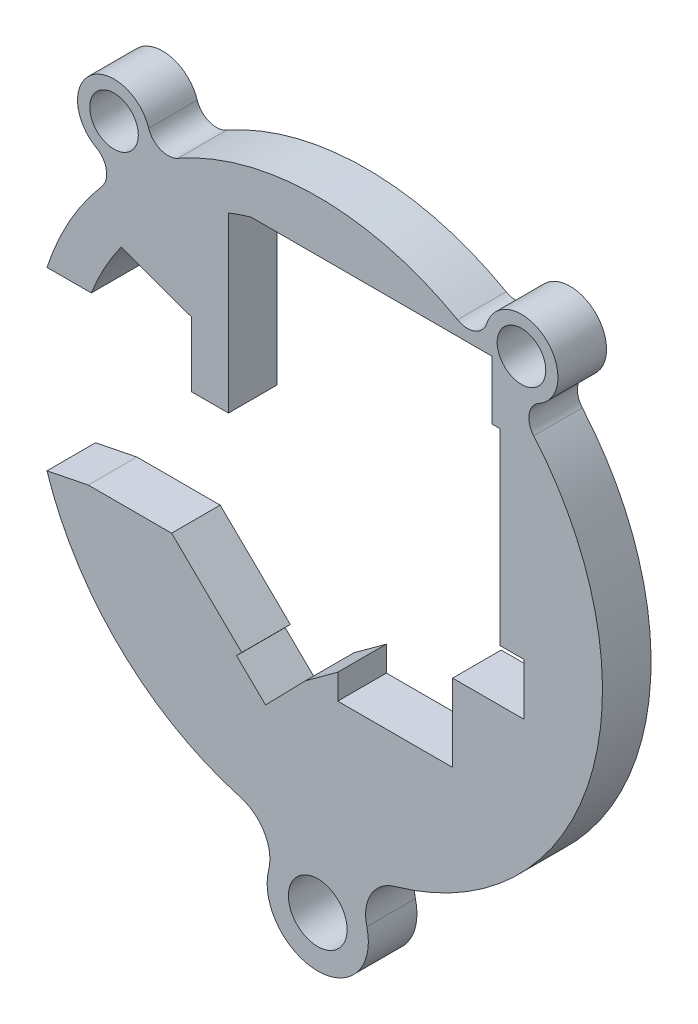
SolidWorks part; units mm, degrees
ref_plane "Front Plane" through (0, 0, 0) normal (0, 0, 1) x (1, 0, 0)
ref_plane "Top Plane" through (0, 0, 0) normal (0, 1, 0) x (1, 0, 0)
ref_plane "Right Plane" through (0, 0, 0) normal (1, 0, 0) x (0, 0, -1)
sketch "Sketch1" plane through (0, 0, 0) normal (0, 0, 1) x (1, 0, 0)
  line L1 (-14.9521, -2.9485) -> (-16.9841, -2.9485)
  line L2 (-16.9841, 2.9485) -> (-16.9841, 5.5245)
  line L3 (-14.9521, 2.9485) -> (-16.9841, 2.9485)
  line L4 (-16.9841, 5.5245) -> (-21.1739, 5.5245)
  line L5 (-16.9841, -2.9485) -> (-16.9841, -5.5245)
  line L6 (-16.9841, -5.5245) -> (-20.8712, -5.5245)
  line L7 (-15.24, 0) -> (-21.59, 0) construction
  line B0 (-15.24, 18.2372) -> (15.24, 18.2372)
  line B1 (11.43, 14.6558) -> (11.43, -0.8128)
  line B2 (0, 18.2372) -> (0, 0) construction
  line B3 (-5.6007, 14.1736) -> (-5.6007, -0.8128)
  line B4 (11.43, 14.6558) -> (-4.1791, 14.6558)
  line B5 (-5.6007, -0.8128) -> (11.43, -0.8128)
  line B6 (8.4582, -4.064) -> (12.9413, -4.064)
  line B7 (11.43, -0.8128) -> (12.9413, -0.8128)
  line B8 (12.9413, -0.8128) -> (12.9413, -4.064)
  line B9 (8.4582, -7.3406) -> (1.2573, -7.3406)
  line B10 (8.4582, -4.064) -> (8.4582, -7.3406)
  line B11 (-4.3942, -0.8128) -> (-4.3942, -4.064)
  line B12 (-4.3942, -4.064) -> (1.2573, -4.064)
  line B13 (1.2573, -4.064) -> (1.2573, -7.3406)
  line B14 (-0.7747, -8.8265) -> (-3.2737, -11.3919)
  line B15 (-0.7747, -8.8265) -> (-2.5941, -7.0541)
  line B16 (-2.5941, -7.0541) -> (-2.9176, -7.3862)
  line B17 (-2.9176, -7.3862) -> (-8.5123, -1.9362)
  line B18 (-8.5123, -1.9362) -> (-10.3645, -3.8375)
  line B19 (-10.3645, -3.8375) -> (-4.7697, -9.2875)
  line B20 (-4.7697, -9.2875) -> (-5.0932, -9.6195)
  line B21 (-5.0932, -9.6195) -> (-3.2737, -11.3919)
  line B22 (-12.3326, 18.2372) -> (-12.3326, 8.9535)
  line B23 (-7.9248, 18.2372) -> (-7.9248, 7.366) construction
  line B24 (-12.3326, 8.9535) -> (-7.9248, 7.366)
  line B25 (-5.6007, 3.302) -> (-7.9248, 3.302)
  line B26 (-7.9248, 3.302) -> (-7.9248, 7.366)
  line B27 (-14.3951, -5.0038) -> (-9.1672, -5.0038)
  line B28 (-0.7747, -8.8265) -> (1.2573, -7.3406)
  arc B29 (-3.302, 14.878) -> (3.302, 14.878) centre (0, 0) ccw
  circle B30 centre (0, -18.415) radius 1.4224
  circle B31 centre (0, 18.415) radius 1.4224
  circle B32 centre (0, 0) radius 21.59
  line B33 (1.2573, -8.9154) -> (8.4582, -8.9154)
  line B34 (1.2573, -7.3406) -> (1.2573, -8.9154)
  line B35 (8.4582, -7.3406) -> (8.4582, -8.9154)
  dimension "D1" = 2.032
  dimension "D2" = 11.049
sketch_block_instance "Block1-1"
sketch_block "Block1" parameters "D1"=3.81, "D2"=30.48, "D3"=3.5814, "D4"=9.6393, "D5"=19.05, "D6"=22.3012, "D7"=1.5113, "D8"=4.4831, "D9"=6.5278, "D10"=7.2009, "D11"=5.6515, "D12"=27.0637, "D13"=29.6291, "D14"=3.5814, "D15"=14.4653, "D16"=2.54, "D17"=2.6543, "D18"=10.3505, "D19"=9.2837, "D20"=10.8712, "D21"=7.3152, "D22"=14.9352, "D23"=23.241
extrude "Boss-Extrude1" add sketch "Sketch1" along normal blind 3.048
sketch "Sketch2" plane through (0, 0, 3.048) normal (0, 0, 1) x (1, 0, 0)
  line L0 (-14.3951, -5.0038) -> (-16.9841, -5.5245)
  line L2 (-16.9841, 5.5245) -> (-14.2034, 5.5245)
  line L3 (-14.3951, -5.0038) -> (-14.2034, 5.5245)
  line L4 (-16.9841, -5.5245) -> (-16.9841, 5.5245)
  arc A0 (-12.3326, 8.9535) -> (-14.9521, 2.9485) centre (0, 0) ccw construction
extrude "Cut-Extrude1" cut sketch "Sketch2" against normal through all
sketch "Sketch3" plane through (0, 0, 3.048) normal (0, 0, 1) x (1, 0, 0)
  line L0 (0, 0) -> (11.43, 14.6558) construction
  line L1 (0, 0) -> (-14.0833, 10.9835) construction
  line L2 (0, 0) -> (-10.9835, -14.0833) construction
  line L3 (0, 0) -> (14.0833, -10.9835) construction
  circle A0 centre (0, 0) radius 17.86
  circle A1 centre (0, 0) radius 21.59
extrude "Cut-Extrude2" cut sketch "Sketch3" against normal through all
sketch "Sketch4" plane through (0, 0, 3.048) normal (0, 0, 1) x (1, 0, 0)
  line L0 (0, -21.035) -> (0, 0) construction
  line L6 (10.2071, 14.6558) -> (11.43, 14.6558)
  line L7 (11.43, 14.6558) -> (11.43, 13.7235)
  line L19 (-21.6223, 17.86) -> (27.8478, 17.86) construction
  circle A0 centre (0, 0) radius 17.86
  circle A1 centre (12.7793, 15.574) radius 1.524
  circle A2 centre (-12.7793, 15.574) radius 2.286
  circle A3 centre (12.7793, 15.574) radius 2.286
  circle A4 centre (-14.5094, 12.4672) radius 1.27
  circle A5 centre (-9.3946, 16.6642) radius 1.27
  circle A6 centre (-12.7793, 15.574) radius 1.524
  circle A7 centre (0, -21.035) radius 1.8415
  circle A8 centre (0, -21.035) radius 3.175
  circle A9 centre (9.3946, 16.6642) radius 1.27
  circle A11 centre (14.5094, 12.4672) radius 1.27
  arc A12 (-1.2889, 17.8134) -> (1.2889, 17.8134) centre (0, 18.415) ccw
  arc A13 (-1.2889, 17.8134) -> (1.2889, 17.8134) centre (0, 18.415) ccw construction
  circle A14 centre (5.5404, -19.6332) radius 2.54
  circle A15 centre (-5.5404, -19.6332) radius 2.54
  arc M3 (-1.2889, -17.8134) -> (1.2889, -17.8134) centre (0, -18.415) cw
  arc M4 (1.2889, -17.8134) -> (11.43, 13.7235) centre (0, 0) ccw
  dimension "D2" = 3.048
  dimension "D4" = 2.54
  dimension "D3" = 3.683
  dimension "D1" = 4.572
  dimension "D5" = 6.35
  dimension "D6" = 5.08
extrude "Boss-Extrude3" add sketch "Sketch4" against normal blind 3.048 contours A5 A2 A0 | A2 A6 | A4 A0 A2 | A0 A12 | A9 A0 L6 A3 | L7 A3 L6 A1 | A11 A3 L7 A0 | A8 A7 | A15 A8 A0 | A14 A0 A8 M4 | A0 M3
sketch "Sketch7" plane through (0, 0, 3.048) normal (0, 0, 1) x (1, 0, 0)
  line L1 (11.43, 14.6558) -> (10.922, 14.6558)
  line L2 (11.43, 14.6558) -> (11.43, 10.9728)
  line L3 (11.43, 10.9728) -> (10.922, 10.9728)
  line L4 (10.922, 14.6558) -> (10.922, 10.9728)
  dimension "D1" = 0.508
  dimension "D2" = 3.683
extrude "Boss-Extrude4" add sketch "Sketch7" against normal up to vertex (3.048 mm away) up to point (11.43, 14.6558, 0)
sketch "Sketch8" plane through (0, 0, 3.048) normal (0, 0, 1) x (1, 0, 0)
  line L0 (-15.24, 18.2372) -> (15.24, 18.2372) construction
  line L1 (-15.24, 18.2372) -> (15.24, 18.2372)
  line L2 (0, 18.2372) -> (0, -12.1158) construction
  line L3 (10.8325, 18.2372) -> (10.8325, -6.5024) construction
  line L4 (0, 0) -> (14.5917, -10.2986) construction
  line L5 (-8.579, 11.2522) -> (-8.579, 18.2372) construction
  circle A0 centre (0, -13.2588) radius 1.143
  circle A1 centre (10.8325, -7.6454) radius 1.143
  arc A2 (4.8506, -17.1887) -> (13.5462, 11.6395) centre (0, 0) ccw construction
  circle A3 centre (-8.579, 10.1092) radius 1.143
  circle A4 centre (0, 0) radius 15.2591 construction
  circle A5 centre (0, 0) radius 13.2588 construction
  dimension "D2" = 2.286
  dimension "D4" = 6.985
  dimension "D5" = 30.5181
  dimension "D1" = 30.353
  dimension "D3" = 24.7396
extrude "Cut-Extrude3" [suppressed] cut sketch "Sketch8" against normal through all contours A0 | A1 | A3
sketch "Sketch9" plane through (0, 0, 3.048) normal (0, 0, 1) x (1, 0, 0)
  line B0 (-12.3326, 8.9535) -> (-7.9248, 7.366)
  line B1 (-7.9248, 3.302) -> (-7.9248, 7.366)
  line B2 (-14.2034, 5.5245) -> (-16.9841, 5.5245)
  line B3 (-16.9841, -5.5245) -> (-14.3951, -5.0038)
  line B4 (-14.3951, -5.0038) -> (-9.1672, -5.0038)
  line B5 (-9.1672, -5.0038) -> (-4.7697, -9.2875)
  line B6 (-4.7697, -9.2875) -> (-5.0932, -9.6195)
  line B7 (-5.0932, -9.6195) -> (-3.2737, -11.3919)
  line B8 (-0.7747, -8.8265) -> (-3.2737, -11.3919)
  line B9 (-0.7747, -8.8265) -> (1.2573, -7.3406)
  line B10 (1.2573, -7.3406) -> (1.2573, -8.9154)
  line B11 (1.2573, -8.9154) -> (8.4582, -8.9154)
  line B12 (8.4582, -4.064) -> (8.4582, -8.9154)
  line B13 (8.4582, -4.064) -> (12.9413, -4.064)
  line B14 (12.9413, -0.8128) -> (12.9413, -4.064)
  line B15 (11.43, -0.8128) -> (12.9413, -0.8128)
  line B16 (11.43, 10.9728) -> (11.43, -0.8128)
  line B17 (10.922, 10.9728) -> (11.43, 10.9728)
  line B18 (10.922, 14.6558) -> (10.922, 10.9728)
  line B19 (-4.1791, 14.6558) -> (10.922, 14.6558)
  line B20 (-5.6007, 14.1736) -> (-5.6007, 3.302)
  line B21 (-5.6007, 3.302) -> (-7.9248, 3.302)
  circle B22 centre (-8.579, 10.1092) radius 1.143
  arc B23 (-12.3326, 8.9535) -> (-14.2034, 5.5245) centre (0, 0) ccw
  arc B24 (-4.1791, 14.6558) -> (-5.6007, 14.1736) centre (0, 0) ccw
  circle B25 centre (10.8325, -7.6454) radius 1.143
  circle B26 centre (0, -13.2588) radius 1.143
sketch_block_instance "Block2-1"
sketch_block "Block2"
